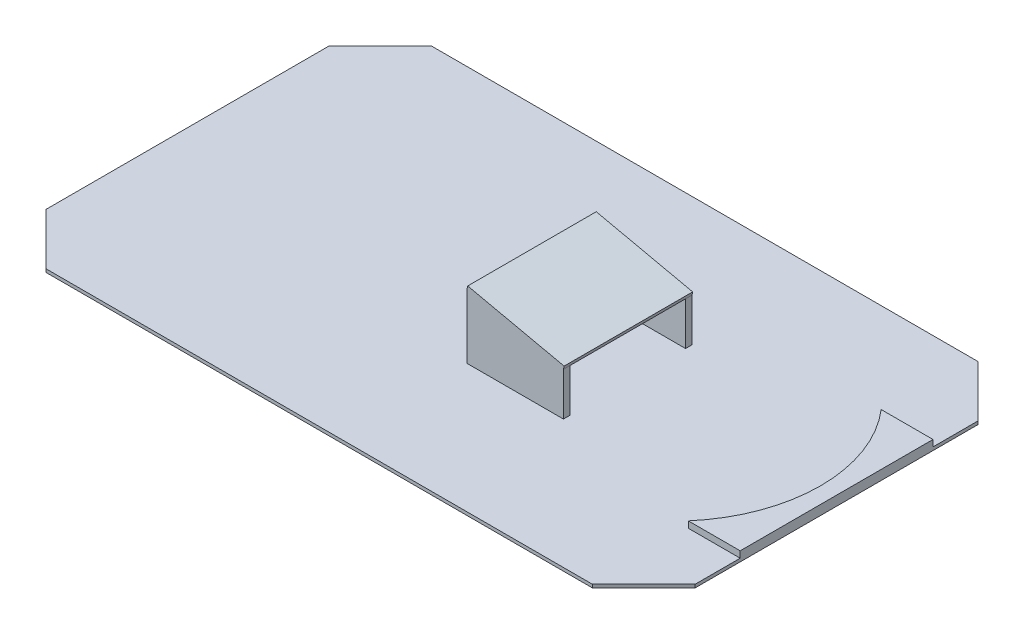
SolidWorks part; units mm, degrees
ref_plane "前视基准面" through (0, 0, 0) normal (0, 0, 1) x (1, 0, 0)
ref_plane "上视基准面" through (0, 0, 0) normal (0, 1, 0) x (1, 0, 0)
ref_plane "右视基准面" through (0, 0, 0) normal (1, 0, 0) x (0, 0, -1)
sketch "草图1" plane through (0, 0, 0) normal (0, 1, 0) x (1, 0, 0)
  line L2 (-505, -50) -> (-505, 220)
  line L3 (-505, -50) -> (-505, -220)
  line L4 (-425, 300) -> (425, 300)
  line L5 (505, 220) -> (505, -10)
  line L6 (505, -10) -> (505, -220)
  line L7 (425, -300) -> (-425, -300)
  line L8 (425, 300) -> (505, 220)
  line L9 (-505, 220) -> (-425, 300)
  line L10 (-505, -220) -> (-425, -300)
  line L11 (505, -220) -> (425, -300)
  point P4 (-505, 300)
  point P5 (505, 300)
  point P6 (-505, -300)
  point P8 (505, -300)
  dimension "D2" = 440
  dimension "D3" = 220
  dimension "D8" = 425
  dimension "D9" = 850
extrude "凸台-拉伸1" add sketch "草图1" along normal blind 5
sketch "草图4" plane through (0, 5, 0) normal (0, 1, 0) x (1, 0, 0)
  line L0 (0, 0) -> (-250, 0) construction
  line L1 (0, 0) -> (250, 0) construction
  line L6 (0, 0) -> (0, 66.9934)
  line L9 (-250, 230) -> (250, 230)
  line L10 (250, 110) -> (-250, 110)
  line L11 (-250, -110) -> (250, -110)
  line L12 (250, -230) -> (-250, -230)
  circle A0 centre (-250, 0) radius 100 construction
  circle A1 centre (250, 0) radius 100 construction
  arc A2 (-250, 110) -> (-250, -110) centre (-250, 0) ccw
  arc A3 (-250, 230) -> (-250, -230) centre (-250, 0) ccw
  arc A4 (250, 110) -> (250, -110) centre (250, 0) cw
  arc A5 (250, 230) -> (250, -230) centre (250, 0) cw
sketch "草图5" plane through (0, 5, 0) normal (0, 1, 0) x (1, 0, 0)
  line L0 (0, 0) -> (100, 0) construction
  line L1 (90, 0) -> (90, -10)
  line L2 (90, -10) -> (110, -10)
  line L8 (100, 0) -> (90, 0) construction
  line L9 (90, 0) -> (90, 10)
  line L10 (90, 10) -> (110, 10)
  line L11 (110, 10) -> (110, -10)
extrude "凸台-拉伸5" add sketch "草图5" along normal blind 30
sketch "草图6" plane through (0, 35, 0) normal (0, 1, 0) x (1, 0, 0)
  line L4 (100, -25) -> (125, -25)
  line L5 (125, -25) -> (125, 25)
  line L6 (125, 25) -> (75, 25)
  line L7 (75, 25) -> (75, -25)
  line L8 (75, -25) -> (100, -25)
extrude "凸台-拉伸6" add sketch "草图6" along normal blind 30
sketch "草图7" plane through (125, 0, 0) normal (1, 0, 0) x (0, 0, -1)
  line L0 (0, 57.5) -> (-7.5, 57.5)
  line L2 (-7.5, 57.5) -> (-7.5, 42.5)
  line L8 (-7.5, 42.5) -> (7.5, 42.5)
  line L9 (7.5, 42.5) -> (7.5, 57.5)
  line L10 (0, 57.5) -> (7.5, 57.5)
extrude "切除-拉伸1" cut sketch "草图7" against normal blind 50
sketch "草图8" plane through (0, 5, 0) normal (0, 1, 0) x (1, 0, 0)
  line L1 (505, -220) -> (505, 220) construction
  line L2 (505, 0) -> (505, 150)
  line L4 (424.356, 150) -> (505, 150)
  line L5 (424.356, -150) -> (505, -150)
  line L6 (505, 0) -> (505, -150)
  arc A0 (424.356, -150) -> (424.356, 150) centre (250, 0) ccw
extrude "凸台-拉伸7" add sketch "草图8" along normal blind 10
sketch "草图9" plane through (0, 5, 0) normal (0, 1, 0) x (1, 0, 0)
  line L0 (0, 0) -> (0, 280)
  circle A0 centre (0, 280) radius 20
sketch "草图12" plane through (0, 5, 0) normal (0, 1, 0) x (1, 0, 0)
  line L0 (0, 0) -> (100, 0) construction
  line L2 (30, -90) -> (100, -90)
  line L3 (100, 100) -> (30, 100)
  line L5 (30, 90) -> (100, 90)
  line L7 (100, -100) -> (30, -100)
  line L9 (100, 100) -> (180, 100)
  line L10 (180, 100) -> (180, 90)
  line L11 (180, 90) -> (100, 90)
  line L12 (100, -90) -> (180, -90)
  line L13 (180, -90) -> (180, -100)
  line L14 (180, -100) -> (100, -100)
  line L16 (30, -90) -> (30, -100)
  line L18 (30, 90) -> (30, 100)
extrude "凸台-拉伸9" add sketch "草图12" along normal blind 100
sketch "草图13" plane through (0, 0, 100) normal (0, 0, 1) x (1, 0, 0)
  line L0 (180, 105) -> (180, 72)
  line L1 (180, 105) -> (180, 5) construction
  line L4 (180, 105) -> (30, 105)
  line L5 (30, 105) -> (180, 105) construction
  line L6 (30, 105) -> (180, 72)
extrude "切除-拉伸2" cut sketch "草图13" against normal through all
sketch "草图15" plane through (23.4185, 106.4479, 0) normal (0.2149, 0.9766, 0) x (0.9766, -0.2149, 0)
  line L2 (160.326, 100) -> (160.326, -100)
  line L4 (160.326, -100) -> (6.7388, -100)
  line L5 (6.7388, -100) -> (6.7388, 100)
  line L6 (6.7388, 100) -> (160.326, 100)
extrude "凸台-拉伸11" add sketch "草图15" along normal blind 5
sketch "草图16" plane through (24.4929, 111.3311, 0) normal (0.2149, 0.9766, 0) x (0.9766, -0.2149, 0)
  line L0 (160.326, 0) -> (110.326, 0)
  line L1 (160.326, -100) -> (160.326, 100) construction
  circle A0 centre (110.326, 0) radius 20
sketch "草图17" plane through (0, 0, 0) normal (0, -1, 0) x (1, 0, 0)
  line L0 (505, 220) -> (483.7868, 198.7868)
  line L1 (483.7868, 198.7868) -> (469.6447, 212.9289)
  line L2 (469.6447, 212.9289) -> (490.8579, 234.1421)
  line L3 (425, 300) -> (505, 220) construction
  line L4 (490.8579, 234.1421) -> (505, 220)
  circle A0 centre (487.3223, 216.4645) radius 10
sketch "草图18" plane through (0, 0, 0) normal (0, -1, 0) x (1, 0, 0)
  line L0 (505, -220) -> (483.7868, -198.7868)
  line L1 (483.7868, -198.7868) -> (469.6447, -212.9289)
  line L2 (469.6447, -212.9289) -> (490.8579, -234.1421)
  line L3 (505, -220) -> (425, -300) construction
  line L4 (490.8579, -234.1421) -> (505, -220)
  circle A0 centre (487.3223, -216.4645) radius 10
sketch "草图19" plane through (0, 0, 0) normal (0, -1, 0) x (1, 0, 0)
  line L0 (-505, 220) -> (-483.7868, 198.7868)
  line L1 (-483.7868, 198.7868) -> (-469.6447, 212.9289)
  line L2 (-469.6447, 212.9289) -> (-490.8579, 234.1421)
  line L3 (-505, 220) -> (-425, 300) construction
  line L4 (-490.8579, 234.1421) -> (-505, 220)
  line L5 (-425, 300) -> (-403.7868, 278.7868)
  line L6 (-403.7868, 278.7868) -> (-417.9289, 264.6447)
  line L7 (-417.9289, 264.6447) -> (-439.1421, 285.8579)
  line L8 (-439.1421, 285.8579) -> (-425, 300)
  line L9 (-505, -220) -> (-483.7868, -198.7868)
  line L10 (-483.7868, -198.7868) -> (-469.6447, -212.9289)
  line L11 (-469.6447, -212.9289) -> (-490.8579, -234.1421)
  line L12 (-425, -300) -> (-505, -220) construction
  line L13 (-490.8579, -234.1421) -> (-505, -220)
  line L14 (-427.1937, -297.8063) -> (-405.9805, -276.5931)
  line L15 (-405.9805, -276.5931) -> (-420.1226, -262.4509)
  line L16 (-420.1226, -262.4509) -> (-441.3358, -283.6642)
  line L17 (-441.3358, -283.6642) -> (-427.1937, -297.8063)
  line L18 (426.6646, -298.3354) -> (405.4514, -277.1222)
  line L19 (505, -220) -> (425, -300) construction
  line L20 (405.4514, -277.1222) -> (419.5936, -262.98)
  line L21 (419.5936, -262.98) -> (440.8068, -284.1932)
  line L22 (440.8068, -284.1932) -> (426.6646, -298.3354)
  line L23 (425, 300) -> (403.7868, 278.7868)
  line L24 (403.7868, 278.7868) -> (417.9289, 264.6447)
  line L25 (417.9289, 264.6447) -> (439.1421, 285.8579)
  line L26 (425, 300) -> (505, 220) construction
  line L27 (439.1421, 285.8579) -> (425, 300)
  line L28 (414.3934, 289.3934) -> (428.5355, 275.2513)
  line L29 (430.2002, -273.5866) -> (416.058, -287.7288)
  line L30 (-416.5871, -287.1997) -> (-430.7292, -273.0576)
  line L31 (-480.2513, -223.5355) -> (-494.3934, -209.3934)
  line L32 (-494.3934, 209.3934) -> (-480.2513, 223.5355)
  line L33 (-428.5355, 275.2513) -> (-414.3934, 289.3934)
  circle A0 centre (-421.4645, 282.3223) radius 10
  circle A1 centre (-487.3223, 216.4645) radius 10
  circle A2 centre (-487.3223, -216.4645) radius 10
  circle A3 centre (-423.6582, -280.1286) radius 10
  circle A4 centre (423.1291, -280.6577) radius 10
  circle A5 centre (421.4645, 282.3223) radius 10
